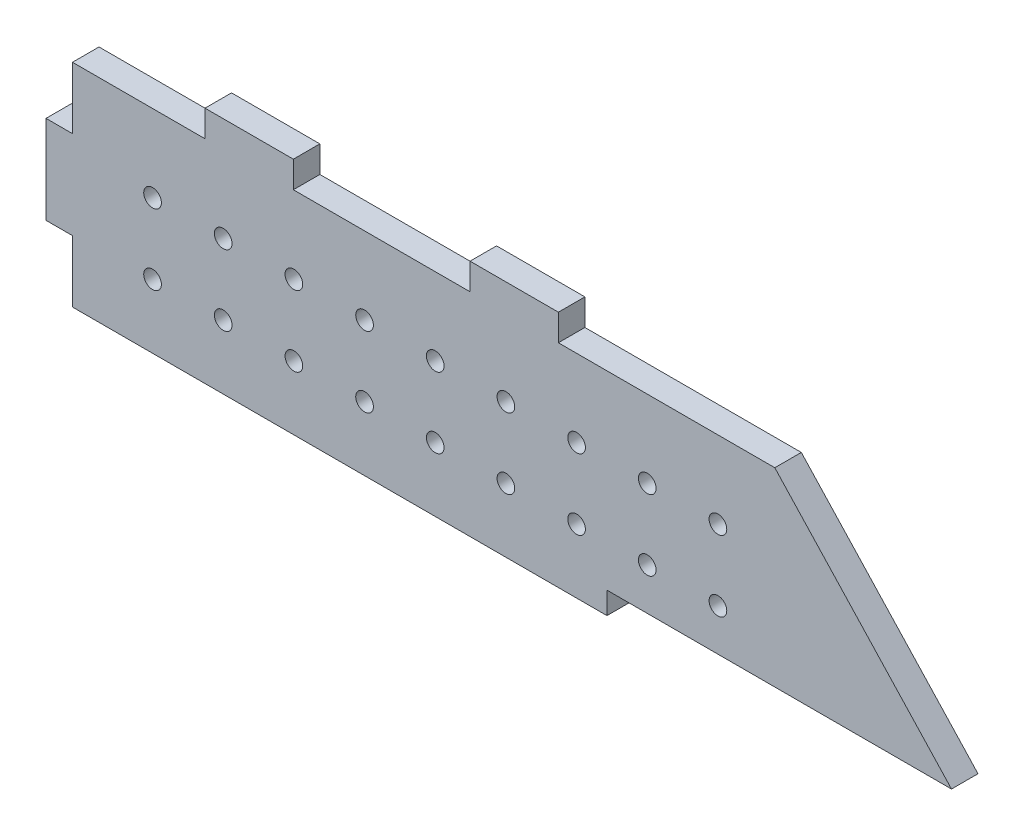
SolidWorks part; units mm, degrees
ref_plane "Plan de face" through (0, 0, 0) normal (0, 0, 1) x (1, 0, 0)
ref_plane "Plan de dessus" through (0, 0, 0) normal (0, 1, 0) x (1, 0, 0)
ref_plane "Plan de droite" through (0, 0, 0) normal (1, 0, 0) x (0, 0, -1)
sketch "Esquisse1" plane through (0, 0, 0) normal (0, 0, 1) x (1, 0, 0)
  line L1 (0, 0) -> (-199, 0)
  line L2 (0, 0) -> (0, 48)
  line L3 (0, 48) -> (-199, 48)
  line L4 (-199, 0) -> (-199, 48)
  dimension "D1" = 48
  dimension "D2" = 199
extrude "Boss.-Extru.1" add sketch "Esquisse1" along normal blind 6
sketch "Esquisse2" plane through (0, 48, 0) normal (0, 1, 0) x (1, 0, 0)
  line L0 (0, -6) -> (-199, -6) construction
  line L1 (-89, -6) -> (-109, -6)
  line L2 (-89, -6) -> (-89, 0)
  line L3 (-89, 0) -> (-109, 0)
  line L4 (-109, -6) -> (-109, 0)
  line L5 (0, 0) -> (-199, 0) construction
  line L6 (-199, -6) -> (-199, 0) construction
  line L7 (-149, -6) -> (-169, -6)
  line L8 (-149, -6) -> (-149, 0)
  line L9 (-149, 0) -> (-169, 0)
  line L10 (-169, -6) -> (-169, 0)
  dimension "D1" = 20
  dimension "D2" = 20
  dimension "D3" = 40
  dimension "D4" = 30
extrude "Boss.-Extru.2" add sketch "Esquisse2" along normal blind 6
sketch "Esquisse3" plane through (-199, 0, 0) normal (-1, 0, 0) x (0, 0, 1)
  line L1 (6, 48) -> (6, 0) construction
  line L2 (6, 34) -> (0, 34)
  line L3 (6, 34) -> (6, 14)
  line L4 (6, 14) -> (0, 14)
  line L6 (0, 34) -> (0, 14)
  line L7 (0, 48) -> (0, 0) construction
  line L8 (6, 48) -> (0, 48) construction
  dimension "D1" = 20
  dimension "D2" = 14
extrude "Boss.-Extru.3" add sketch "Esquisse3" along normal blind 6
sketch "Esquisse4" plane through (0, 0, 6) normal (0, 0, 1) x (1, 0, 0)
  line L1 (0, 0) -> (-78, 0)
  line L2 (0, 0) -> (0, 5)
  line L3 (0, 5) -> (-78, 5)
  line L4 (-78, 0) -> (-78, 5)
  dimension "D1" = 5
  dimension "D2" = 78
extrude "Enlèv. mat.-Extru.1" cut sketch "Esquisse4" against normal through all
sketch "Esquisse5" plane through (0, 0, 6) normal (0, 0, 1) x (1, 0, 0)
  line L0 (0, 48) -> (-40, 48)
  line L1 (0, 48) -> (-89, 48) construction
  line L2 (-40, 48) -> (0, 5)
  line L3 (0, 5) -> (0, 48)
  dimension "D1" = 159
extrude "Enlèv. mat.-Extru.2" cut sketch "Esquisse5" against normal through all
sketch "Esquisse6" plane through (0, 0, 6) normal (0, 0, 1) x (1, 0, 0)
  line L0 (-199, 0) -> (-78, 0) construction
  line L1 (-199, 14) -> (-199, 0) construction
  line L2 (-199, 48) -> (-199, 34) construction
  line L3 (-148.88, 14.5) -> (-164.88, 14.5) construction
  circle A0 centre (-148.88, 14.5) radius 1.005
  circle A1 centre (-148.88, 30.5) radius 1.005
  circle A2 centre (-132.88, 14.5) radius 1.005
  circle A3 centre (-132.88, 30.5) radius 1.005
  circle A4 centre (-116.88, 14.5) radius 1.005
  circle A5 centre (-116.88, 30.5) radius 1.005
  circle A6 centre (-100.88, 14.5) radius 1.005
  circle A7 centre (-100.88, 30.5) radius 1.005
  circle A8 centre (-84.88, 14.5) radius 1.005
  circle A9 centre (-84.88, 30.5) radius 1.005
  circle A10 centre (-68.88, 14.5) radius 1.005
  circle A11 centre (-68.88, 30.5) radius 1.005
  circle A12 centre (-52.88, 14.5) radius 1.005
  circle A13 centre (-52.88, 30.5) radius 1.005
  circle A14 centre (-164.88, 14.5) radius 1.005
  circle A15 centre (-164.88, 30.5) radius 1.005
  circle A16 centre (-180.88, 14.5) radius 1.005
  circle A17 centre (-180.88, 30.5) radius 1.005
  dimension "D1" = 2.01
  dimension "D2" = 2.01
  dimension "D3" = 2.01
  dimension "D4" = 2.01
  dimension "D12" = 50.12
  dimension "D16" = 14.5
  dimension "D17" = 14.5
  dimension "D18" = 16
  dimension "D5" = 16
  dimension "D6" = 16
  dimension "D7" = 16
  dimension "D8" = 16
  dimension "D9" = 14.5
  dimension "D10" = 50.12
  dimension "D11" = 14.5
  dimension "D15" = 16
  dimension "D13" = 6
  dimension "D14" = 3
extrude "Enlèv. mat.-Extru.3" cut sketch "Esquisse6" against normal through all
sketch "Esquisse7" plane through (0, 0, 6) normal (0, 0, 1) x (1, 0, 0)
  line L0 (-52.88, 14.5) -> (-68.88, 14.5) construction
  line L1 (-199, 0) -> (-78, 0) construction
  circle A0 centre (-52.88, 14.5) radius 2
  circle A1 centre (-52.88, 30.5) radius 2
  circle A2 centre (-68.88, 14.5) radius 2
  circle A3 centre (-68.88, 30.5) radius 2
  circle A4 centre (-84.88, 14.5) radius 2
  circle A5 centre (-84.88, 30.5) radius 2
  circle A6 centre (-100.88, 14.5) radius 2
  circle A7 centre (-100.88, 30.5) radius 2
  circle A8 centre (-116.88, 14.5) radius 2
  circle A9 centre (-116.88, 30.5) radius 2
  circle A10 centre (-132.88, 14.5) radius 2
  circle A11 centre (-132.88, 30.5) radius 2
  circle A12 centre (-148.88, 14.5) radius 2
  circle A13 centre (-148.88, 30.5) radius 2
  circle A14 centre (-164.88, 14.5) radius 2
  circle A15 centre (-164.88, 30.5) radius 2
  circle A16 centre (-180.88, 14.5) radius 2
  circle A17 centre (-180.88, 30.5) radius 2
  dimension "D1" = 4
  dimension "D2" = 4
  dimension "D5" = 14.5
  dimension "D4" = 16
  dimension "D3" = 9
extrude "Enlèv. mat.-Extru.4" cut sketch "Esquisse7" against normal blind 3
